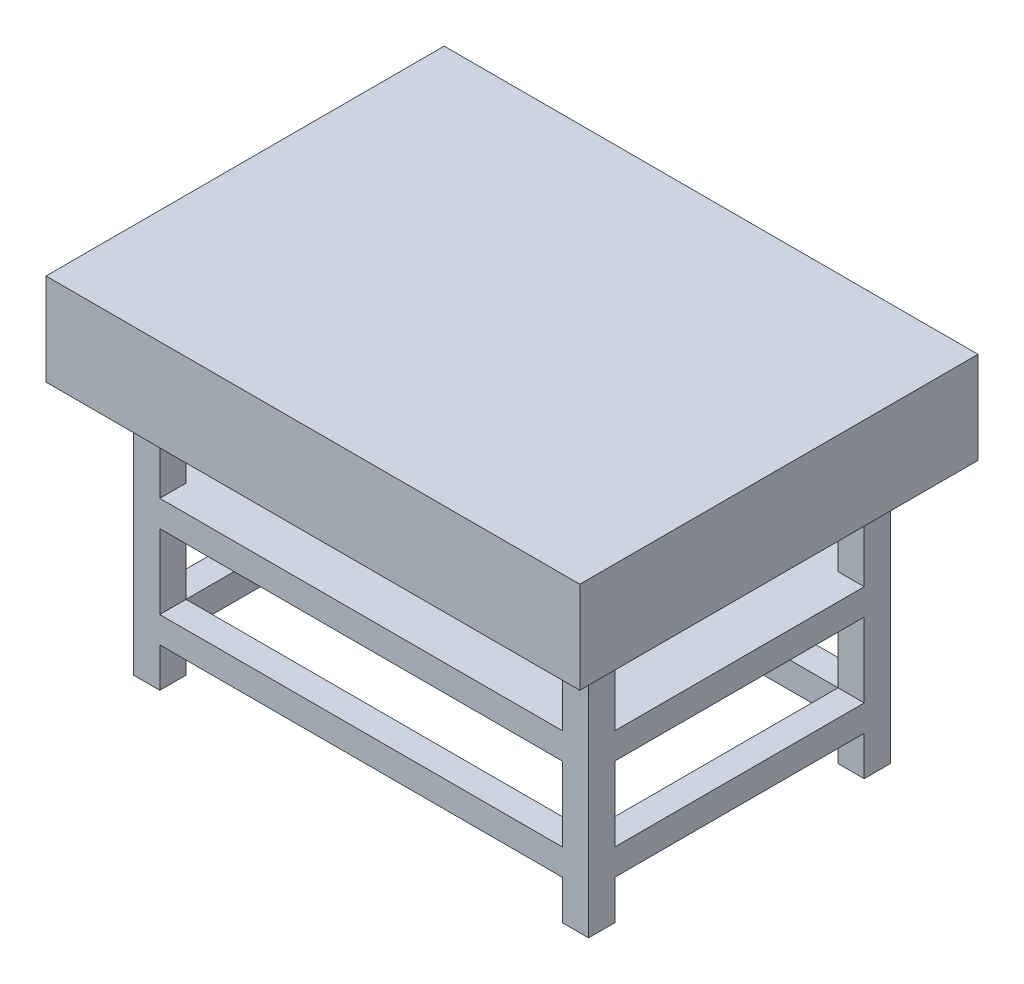
SolidWorks part; units mm, degrees
ref_plane "正面" through (0, 0, 0) normal (0, 0, 1) x (1, 0, 0)
ref_plane "平面" through (0, 0, 0) normal (0, 1, 0) x (1, 0, 0)
ref_plane "右側面" through (0, 0, 0) normal (1, 0, 0) x (0, 0, -1)
sketch "ｽｹｯﾁ1" plane through (0, 0, 0) normal (0, 1, 0) x (1, 0, 0)
  line L1 (0, 0) -> (1220, 0)
  line L2 (0, 0) -> (0, 910)
  line L3 (0, 910) -> (1220, 910)
  line L4 (1220, 0) -> (1220, 910)
  dimension "D1" = 1220
  dimension "D2" = 910
extrude "ﾎﾞｽ - 押し出し1" add sketch "ｽｹｯﾁ1" along normal blind 210
sketch "ｽｹｯﾁ2" plane through (0, 0, 0) normal (0, -1, 0) x (1, 0, 0)
  line L0 (1220, 0) -> (1220, -910) construction
  line L1 (90, -90) -> (150, -90)
  line L2 (90, -90) -> (90, -820)
  line L3 (90, -820) -> (150, -820)
  line L4 (150, -90) -> (150, -820)
  line L5 (1070, -90) -> (1130, -90)
  line L6 (1070, -90) -> (1070, -820)
  line L7 (1070, -820) -> (1130, -820)
  line L8 (1130, -90) -> (1130, -820)
  line L9 (0, 0) -> (1220, 0) construction
  line L10 (1220, -910) -> (0, -910) construction
  line L11 (0, -910) -> (0, 0) construction
  line L13 (150, -110) -> (1070, -110)
  line L14 (150, -110) -> (150, -170)
  line L15 (150, -170) -> (1070, -170)
  line L16 (1070, -110) -> (1070, -170)
  line L17 (150, -740) -> (1070, -740)
  line L18 (150, -740) -> (150, -800)
  line L19 (150, -800) -> (1070, -800)
  line L20 (1070, -740) -> (1070, -800)
  dimension "D1" = 90
  dimension "D2" = 90
  dimension "D3" = 90
  dimension "D4" = 60
  dimension "D5" = 90
  dimension "D6" = 90
  dimension "D7" = 90
  dimension "D8" = 60
  dimension "D9" = 60
  dimension "D10" = 60
  dimension "D11" = 20
  dimension "D12" = 20
extrude "ﾎﾞｽ - 押し出し2" add sketch "ｽｹｯﾁ2" along normal blind 60 contours L4 L1 L2 L3 | L4 L15 L6 L13 | L4 L19 L6 L17 | L8 L5 L6 L7
sketch "ｽｹｯﾁ3" plane through (0, -60, 0) normal (0, -1, 0) x (-1, 0, 0)
  line L1 (-150, 170) -> (-90, 170)
  line L2 (-150, 170) -> (-150, 110)
  line L3 (-150, 110) -> (-90, 110)
  line L4 (-90, 170) -> (-90, 110)
  line L5 (-1070, 170) -> (-1130, 170)
  line L6 (-1070, 170) -> (-1070, 110)
  line L7 (-1070, 110) -> (-1130, 110)
  line L8 (-1130, 170) -> (-1130, 110)
  line L9 (-1070, 740) -> (-1130, 740)
  line L10 (-1070, 740) -> (-1070, 800)
  line L11 (-1070, 800) -> (-1130, 800)
  line L12 (-1130, 740) -> (-1130, 800)
  line L13 (-150, 740) -> (-90, 740)
  line L14 (-150, 740) -> (-150, 800)
  line L15 (-150, 800) -> (-90, 800)
  line L16 (-90, 740) -> (-90, 800)
  dimension "D1" = 60
  dimension "D2" = 60
  dimension "D3" = 60
  dimension "D4" = 60
  dimension "D5" = 60
  dimension "D6" = 60
  dimension "D7" = 60
  dimension "D8" = 60
extrude "ﾎﾞｽ - 押し出し3" add sketch "ｽｹｯﾁ3" along normal blind 530
sketch "ｽｹｯﾁ4" plane through (0, 0, -170) normal (0, 0, -1) x (-1, 0, 0)
  line L0 (-150, -590) -> (-150, -60) construction
  line L1 (-150, -440) -> (-90, -440)
  line L2 (-150, -440) -> (-150, -500)
  line L3 (-150, -500) -> (-90, -500)
  line L4 (-90, -440) -> (-90, -500)
  line L5 (-90, -590) -> (-90, -60) construction
  line L6 (-1130, -590) -> (-1130, -60) construction
  line L7 (-150, -210) -> (-90, -210)
  line L8 (-150, -210) -> (-150, -270)
  line L9 (-150, -270) -> (-90, -270)
  line L10 (-90, -210) -> (-90, -270)
  line L11 (-1130, -210) -> (-1070, -210)
  line L12 (-1130, -210) -> (-1130, -270)
  line L13 (-1130, -270) -> (-1070, -270)
  line L14 (-1070, -210) -> (-1070, -270)
  line L15 (-1070, -590) -> (-1070, -60) construction
  line L16 (-90, -590) -> (-150, -590) construction
  line L17 (-1130, -440) -> (-1070, -440)
  line L18 (-1130, -440) -> (-1130, -500)
  line L19 (-1130, -500) -> (-1070, -500)
  line L20 (-1070, -440) -> (-1070, -500)
  line L21 (-1070, -590) -> (-1130, -590) construction
  dimension "D1" = 60
  dimension "D2" = 60
  dimension "D3" = 60
  dimension "D4" = 60
  dimension "D5" = 170
  dimension "D6" = 90
  dimension "D7" = 170
  dimension "D8" = 90
extrude "ﾎﾞｽ - 押し出し4" add sketch "ｽｹｯﾁ4" along normal up to next
sketch "ｽｹｯﾁ5" plane through (150, 0, 0) normal (1, 0, 0) x (0, 0, -1)
  line L1 (740, -500) -> (800, -500)
  line L2 (740, -500) -> (740, -440)
  line L3 (740, -440) -> (800, -440)
  line L4 (800, -500) -> (800, -440)
  line L5 (170, -500) -> (110, -500)
  line L6 (170, -500) -> (170, -440)
  line L7 (170, -440) -> (110, -440)
  line L8 (110, -500) -> (110, -440)
  dimension "D1" = 60
  dimension "D2" = 60
  dimension "D3" = 60
  dimension "D4" = 60
extrude "ﾎﾞｽ - 押し出し5" add sketch "ｽｹｯﾁ5" along normal up to next
sketch "ｽｹｯﾁ6" plane through (1070, 0, 0) normal (-1, 0, 0) x (0, 0, 1)
  line L0 (-800, -440) -> (-800, -60) construction
  line L1 (-110, -210) -> (-800, -210)
  line L2 (-110, -210) -> (-110, -270)
  line L3 (-110, -270) -> (-800, -270)
  line L4 (-800, -210) -> (-800, -270)
  line L5 (-740, -210) -> (-170, -210) construction
  line L6 (-740, -270) -> (-170, -270) construction
  line L7 (-110, -440) -> (-110, -60) construction
extrude "ﾎﾞｽ - 押し出し7" add sketch "ｽｹｯﾁ6" along normal up to surface (980 mm away) up to face at (90, -153.75, -383.75)
